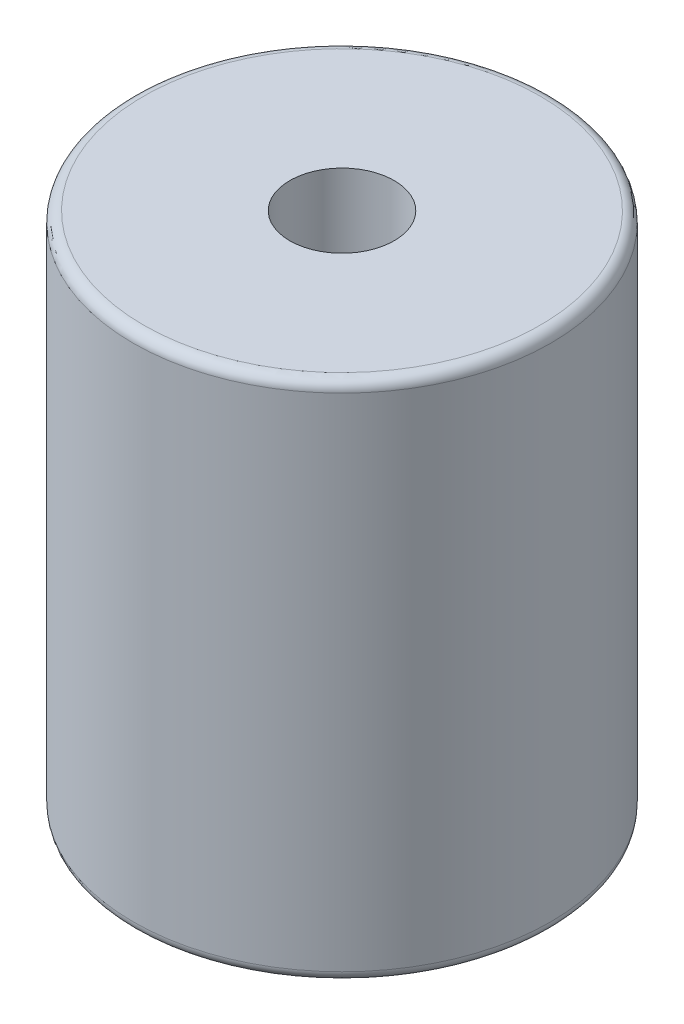
SolidWorks part; units mm, degrees
ref_plane "Front Plane" through (0, 0, 0) normal (0, 0, 1) x (1, 0, 0)
ref_plane "Top Plane" through (0, 0, 0) normal (0, 1, 0) x (1, 0, 0)
ref_plane "Right Plane" through (0, 0, 0) normal (1, 0, 0) x (0, 0, -1)
sketch "Sketch1" plane through (0, 0, 0) normal (0, 1, 0) x (1, 0, 0)
  circle A0 centre (0, 0) radius 10
  dimension "D1" = 20
extrude "Boss-Extrude1" add sketch "Sketch1" along normal blind 25
fillet "Fillet2" radius 0.5 1 edges at (0, 25, 10)
fillet "Fillet3" radius 0.5 1 edges at (0, 0, 10)
sketch "Sketch2" plane through (0, 0, 0) normal (0, -1, 0) x (1, 0, 0)
  circle A0 centre (0, 0) radius 4
  dimension "D1" = 8
extrude "Cut-Extrude1" cut sketch "Sketch2" against normal blind 12.5
sketch "Sketch3" plane through (0, 25, 0) normal (0, 1, 0) x (1, 0, 0)
  circle A0 centre (0, 0) radius 2.5
  dimension "D1" = 5
extrude "Cut-Extrude2" cut sketch "Sketch3" against normal blind 12.5
